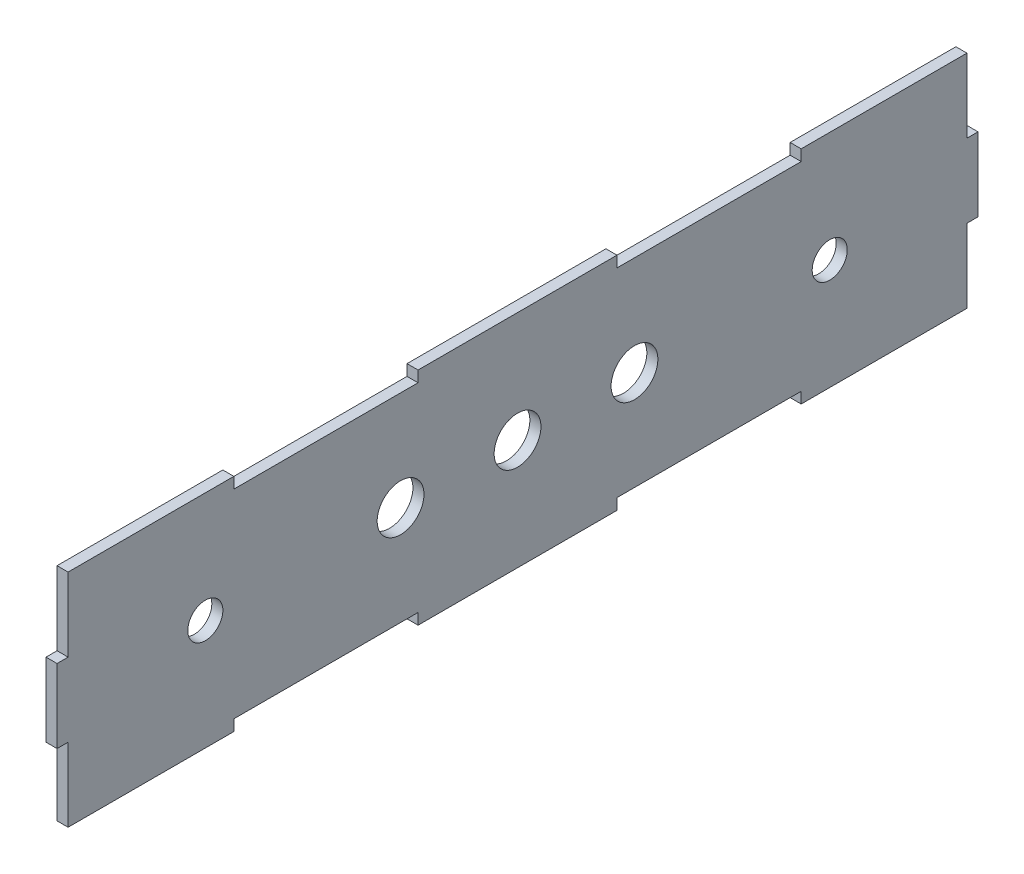
SolidWorks part; units mm, degrees
material "Acrylic (Medium-high impact)"
ref_plane "Alzado" through (0, 0, 0) normal (0, 0, 1) x (1, 0, 0)
ref_plane "Planta" through (0, 0, 0) normal (0, 1, 0) x (1, 0, 0)
ref_plane "Vista lateral" through (0, 0, 0) normal (1, 0, 0) x (0, 0, -1)
sketch "Sketch1" plane through (0, 0, 0) normal (1, 0, 0) x (0, 0, -1)
  line L0 (0, -30) -> (0, 30) construction
  line L1 (-122, 30) -> (-77, 30)
  line L2 (-122, 30) -> (-122, 10)
  line L3 (-122, -30) -> (-77, -30)
  line L4 (125, 10) -> (125, -10)
  line L5 (-122, -10) -> (-122, -30)
  line L6 (122, 30) -> (122, 10)
  line L7 (122, 10) -> (125, 10)
  line L8 (125, 10) -> (125, -10)
  line L9 (125, -10) -> (122, -10)
  line L10 (122, -10) -> (122, -30)
  line L11 (-125, -10) -> (-122, -10)
  line L12 (-125, 10) -> (-125, -10)
  line L13 (-122, 30) -> (-122, 10)
  line L14 (-125, 10) -> (-122, 10)
  line L15 (-122, -10) -> (-122, -30)
  line L16 (-77, 30) -> (-77, 27)
  line L17 (-77, 27) -> (-27, 27)
  line L18 (-27, 27) -> (-27, 30)
  line L19 (27, 30) -> (27, 27)
  line L20 (27, 27) -> (77, 27)
  line L21 (77, 27) -> (77, 30)
  line L22 (-125, 0) -> (125, 0) construction
  line L23 (77, -27) -> (77, -30)
  line L24 (27, -27) -> (77, -27)
  line L25 (27, -30) -> (27, -27)
  line L26 (-27, -27) -> (-27, -30)
  line L27 (-77, -27) -> (-27, -27)
  line L28 (-77, -30) -> (-77, -27)
  line L29 (-122, -30) -> (-77, -30)
  line L30 (-27, 30) -> (27, 30)
  line L31 (77, 30) -> (122, 30)
  line L32 (77, -30) -> (122, -30)
  line L33 (77, -30) -> (122, -30)
  line L34 (-27, -30) -> (27, -30)
  line L35 (-27, -30) -> (27, -30)
  point P0 (0, 0)
  point P27 (0, 0)
  dimension "D1" = 50
  dimension "D2" = 50
  dimension "D3" = 250
  dimension "D4" = 20
  dimension "D5" = 45
  dimension "D6" = 3
  dimension "D7" = 60
  dimension "D8" = 45
  dimension "D9" = 3
  dimension "D10" = 3
extrude "Boss-Extrude1" add sketch "Sketch1" along normal blind 3
sketch "Sketch2" plane through (3, 0, 0) normal (1, 0, 0) x (0, 0, -1)
  line L0 (0, 0) -> (-31.75, 0) construction
  line L1 (0, -13.0555) -> (0, 14.447) construction
  line L2 (-31.75, 0) -> (-84.75, 0) construction
  circle A0 centre (0, 0) radius 6.35
  circle A1 centre (-31.75, 0) radius 6.35
  circle A2 centre (31.75, 0) radius 6.35
  circle A3 centre (-84.75, 0) radius 4.7625
  circle A4 centre (84.75, 0) radius 4.7625
  dimension "D1" = 12.7
  dimension "D2" = 12.7
  dimension "D3" = 12.7
  dimension "D4" = 9.525
  dimension "D5" = 9.525
extrude "Cut-Extrude1" cut sketch "Sketch2" against normal through all
